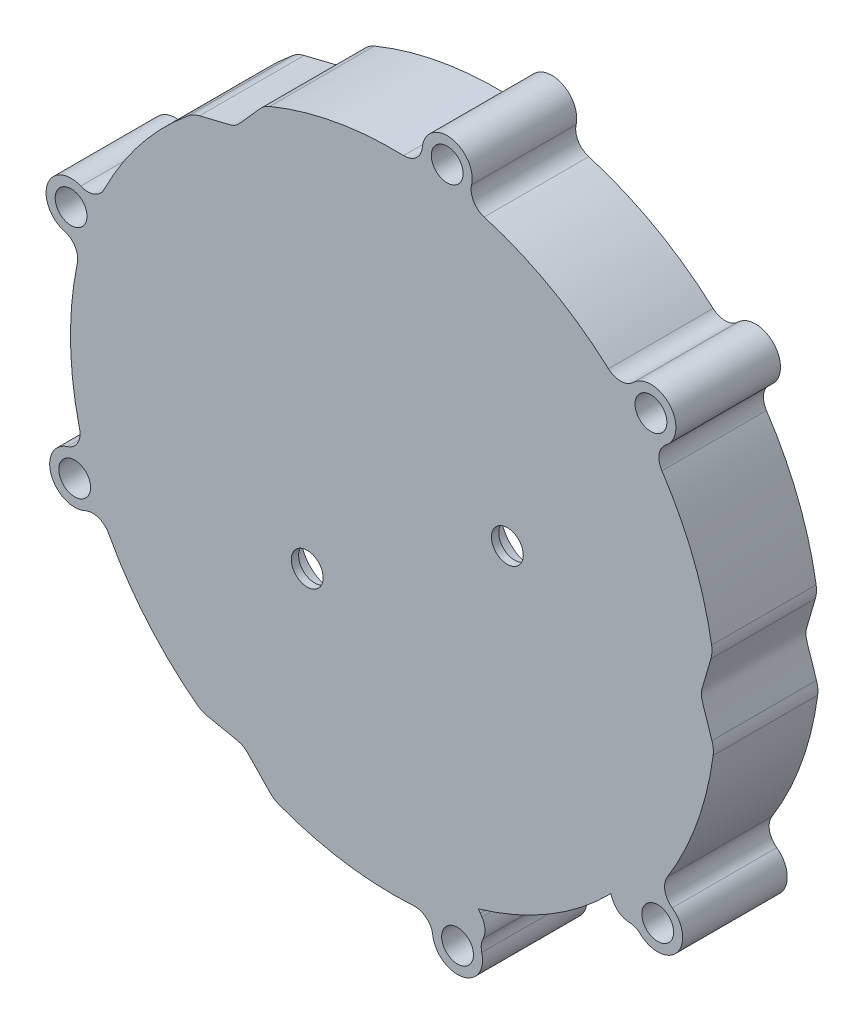
SolidWorks part; units mm, degrees
ref_plane "前视基准面" through (0, 0, 0) normal (0, 0, 1) x (1, 0, 0)
ref_plane "上视基准面" through (0, 0, 0) normal (0, 1, 0) x (1, 0, 0)
ref_plane "右视基准面" through (0, 0, 0) normal (1, 0, 0) x (0, 0, -1)
other "Configuration Table"
sketch "草图3" plane through (0, 0, -96.0145) normal (0, 0, 1) x (1, 0, 0)
  line L0 (-901.3742, -492.7064) -> (-40.5392, 22.1874) construction
  line L1 (-40.493, 24.6873) -> (-40.6757, 24.9625)
  line L3 (-26.0215, 33.3432) -> (-26.1775, 33.6344)
  line L5 (-23.7971, 32.2015) -> (837.0379, 547.0953) construction
  line L6 (-66.9395, 85.3275) -> (-545.4853, 885.3934) construction
  arc A0 (-71.5536, 85.4824) -> (-72.7752, 84.88) centre (-70.8722, 82.5608) ccw
  arc A1 (-64.9322, 89.4483) -> (-63.8246, 90.241) centre (-62.678, 87.4687) cw
  arc A2 (-15.3194, 61.8566) -> (-15.2303, 63.2157) centre (-18.1903, 62.7273) ccw
  arc A3 (-15.0628, 52.7838) -> (-15.1955, 54.1394) centre (-18.037, 53.177) ccw
  arc A4 (-43.4208, 19.0803) -> (-42.9297, 22.1412) centre (-43.1752, 20.6108) ccw
  arc A5 (-42.9297, 22.1412) -> (-43.4208, 19.0803) centre (-43.1752, 20.6108) ccw
  arc A6 (-70.6423, 28.7206) -> (-71.8826, 29.2835) centre (-70.055, 31.6626) cw
  arc A7 (-63.897, 24.9693) -> (-62.7646, 24.2125) centre (-61.7076, 27.0202) ccw
  arc A8 (-20.3655, 32.4479) -> (-21.9568, 35.1083) centre (-21.1611, 33.7781) ccw
  arc A9 (-21.9568, 35.1083) -> (-20.3655, 32.4479) centre (-21.1611, 33.7781) ccw
  arc A10 (-25.9128, 35.9041) -> (-66.9395, 85.3275) centre (-50.2567, 57.4361) ccw
  arc A11 (-66.9395, 85.3275) -> (-42.8007, 25.8029) centre (-50.2567, 57.4361) ccw
  arc A12 (-26.1775, 33.6344) -> (-25.9128, 35.9041) centre (-24.4147, 34.5791) cw
  arc A13 (-26.0215, 33.3432) -> (-24.3219, 32.2889) centre (-24.2586, 34.2879) ccw
  arc A14 (-40.493, 24.6873) -> (-40.368, 22.6912) centre (-42.1592, 23.581) cw
  arc A15 (-40.6757, 24.9625) -> (-42.8007, 25.8029) centre (-42.3419, 23.8562) ccw
  arc A134 (-23.0277, 31.7586) -> (-24.3219, 32.2889) centre (-24.3852, 30.2899) ccw
  arc A135 (-23.0277, 31.7586) -> (-19.7495, 31.4181) centre (-21.1611, 33.7781) ccw
  arc A136 (-19.7495, 31.4181) -> (-19.5648, 36.0174) centre (-21.1611, 33.7781) ccw
  arc A137 (-20.1027, 38.7014) -> (-19.5648, 36.0174) centre (-18.4039, 37.646) ccw
  arc A138 (-20.1027, 38.7014) -> (-15.0628, 52.7838) centre (-50.2567, 57.4361) ccw
  arc A139 (-14.8785, 53.9257) -> (-14.9764, 53.4929) centre (-12.9887, 53.2708) ccw
  arc A140 (-12.8929, 55.2685) -> (-14.8785, 53.9257) centre (-12.9887, 53.2708) ccw
  arc A141 (-12.8929, 55.2685) -> (-10.1628, 57.1148) centre (-12.7612, 58.0153) ccw
  arc A142 (-10.1628, 57.1148) -> (-12.9777, 60.7568) centre (-12.7612, 58.0153) ccw
  arc A143 (-15.115, 62.4671) -> (-12.9777, 60.7568) centre (-13.1352, 62.7506) ccw
  arc A144 (-15.2303, 63.2157) -> (-20.6958, 77.0932) centre (-50.2567, 57.4361) ccw
  arc A145 (-20.899, 77.4877) -> (-20.6958, 77.0932) centre (-19.0304, 78.2006) ccw
  arc A146 (-20.2411, 79.7926) -> (-20.899, 77.4877) centre (-19.0304, 78.2006) ccw
  arc A147 (-20.2411, 79.7926) -> (-19.3364, 82.9618) centre (-21.9058, 81.9815) ccw
  arc A148 (-19.3364, 82.9618) -> (-23.8338, 83.9424) centre (-21.9058, 81.9815) ccw
  arc A149 (-26.5705, 83.8787) -> (-23.8338, 83.9424) centre (-25.236, 85.3685) ccw
  arc A150 (-26.5705, 83.8787) -> (-40.2471, 91.4957) centre (-50.2567, 57.4361) ccw
  arc A151 (-40.6563, 91.6673) -> (-40.2471, 91.4957) centre (-39.6831, 93.4145) ccw
  arc A152 (-41.6339, 93.8558) -> (-40.6563, 91.6673) centre (-39.6831, 93.4145) ccw
  arc A153 (-41.6339, 93.8558) -> (-42.978, 96.8651) centre (-44.3161, 94.4625) ccw
  arc A154 (-42.978, 96.8651) -> (-47.0535, 94.7253) centre (-44.3161, 94.4625) ccw
  arc A155 (-49.109, 92.9175) -> (-47.0535, 94.7253) centre (-49.0443, 94.9165) ccw
  arc A156 (-49.109, 92.9175) -> (-63.8246, 90.241) centre (-50.2567, 57.4361) ccw
  arc A157 (-64.9057, 89.8297) -> (-64.482, 89.9613) centre (-65.2834, 91.7937) ccw
  arc A158 (-67.0614, 90.8779) -> (-64.9057, 89.8297) centre (-65.2834, 91.7937) ccw
  arc A159 (-67.0614, 90.8779) -> (-70.0254, 92.3191) centre (-69.5061, 89.6185) ccw
  arc A160 (-70.0254, 92.3191) -> (-71.772, 88.0603) centre (-69.5061, 89.6185) ccw
  arc A161 (-72.1845, 85.3542) -> (-71.772, 88.0603) centre (-73.4199, 86.927) ccw
  arc A162 (-72.7752, 84.88) -> (-82.0607, 73.208) centre (-50.2567, 57.4361) ccw
  arc A163 (-82.3007, 72.8348) -> (-82.0607, 73.208) centre (-83.8525, 74.0966) ccw
  arc A164 (-84.6258, 72.2521) -> (-82.3007, 72.8348) centre (-83.8525, 74.0966) ccw
  arc A165 (-84.6258, 72.2521) -> (-87.8227, 71.4509) centre (-85.6891, 69.716) ccw
  arc A166 (-87.8227, 71.4509) -> (-86.4232, 67.0658) centre (-85.6891, 69.716) ccw
  arc A167 (-84.9998, 64.7276) -> (-86.4232, 67.0658) centre (-86.9571, 65.1384) ccw
  arc A168 (-84.9998, 64.7276) -> (-84.758, 49.0749) centre (-50.2567, 57.4361) ccw
  arc A169 (-84.702, 48.6347) -> (-84.758, 49.0749) centre (-86.7017, 48.6038) ccw
  arc A170 (-86.1085, 46.6938) -> (-84.702, 48.6347) centre (-86.7017, 48.6038) ccw
  arc A171 (-86.1085, 46.6938) -> (-88.0425, 44.0251) centre (-85.2928, 44.0676) ccw
  arc A172 (-88.0425, 44.0251) -> (-84.1517, 41.5655) centre (-85.2928, 44.0676) ccw
  arc A173 (-81.5583, 40.6893) -> (-84.1517, 41.5655) centre (-83.3218, 39.7458) ccw
  arc A174 (-81.5583, 40.6893) -> (-71.8826, 29.2835) centre (-50.2567, 57.4361) ccw
  arc A175 (-70.9859, 28.5528) -> (-71.3117, 28.854) centre (-72.4979, 27.2437) ccw
  arc A176 (-70.8158, 26.1619) -> (-70.9859, 28.5528) centre (-72.4979, 27.2437) ccw
  arc A177 (-70.8158, 26.1619) -> (-70.5819, 22.8744) centre (-68.5028, 24.6744) ccw
  arc A178 (-70.5819, 22.8744) -> (-66.0204, 23.4912) centre (-68.5028, 24.6744) ccw
  arc A179 (-63.4705, 24.487) -> (-66.0204, 23.4912) centre (-64.215, 22.6307) ccw
  arc A180 (-62.7646, 24.2125) -> (-48.0136, 22.007) centre (-50.2567, 57.4361) ccw
  arc A181 (-47.5704, 21.9858) -> (-48.0136, 22.007) centre (-47.8872, 20.011) ccw
  arc A182 (-45.9032, 20.2635) -> (-47.5704, 21.9858) centre (-47.8872, 20.011) ccw
  arc A183 (-45.9032, 20.2635) -> (-43.6109, 17.8955) centre (-43.1752, 20.6108) ccw
  arc A184 (-43.6109, 17.8955) -> (-40.513, 21.3001) centre (-43.1752, 20.6108) ccw
  arc A185 (-40.368, 22.6912) -> (-40.513, 21.3001) centre (-38.5769, 21.8014) ccw
  conic Q0 (-71.5536, 85.4824) -> (-64.9322, 89.4483) control (-67.6066, 86.4029) rho 0.891852
  conic Q1 (-15.3194, 61.8566) -> (-15.1955, 54.1394) control (-16.4957, 57.9781) rho 0.891852
  conic Q2 (-63.897, 24.9693) -> (-70.6423, 28.7206) control (-66.6678, 27.9272) rho 0.891852
  point P64 (-50.2567, 57.4361)
  dimension "D1" = 3
  dimension "D2" = 3
  dimension "D3" = 3
  dimension "D4" = 3
  dimension "D5" = 3
  dimension "D6" = 3
  dimension "D7" = 2
extrude "凸台-拉伸2" add sketch "草图3" along normal offset from surface (11.5 mm away) 3 contours Q2 A7 A180 A181 A182 A183 A184 A185 A14 L1 A15 A11 A10 A12 L3 A13 A134 A135 A136 A137 A138 A3 Q1 A2 A144 A145 A146 A147 A148 A149 A150 A151 A152 A153 A154 A155 A156 A1 Q0 A0 A162 A163 A164 A165 A166 A167 A168 A169 A170 A171 A172
sketch "草图5" plane through (0, 0, -84.5145) normal (0, 0, 1) x (1, 0, 0)
  arc A0 (-25.9128, 35.9041) -> (-42.8007, 25.8029) centre (-50.2567, 57.4361) ccw construction
  arc A1 (-25.9128, 35.9041) -> (-42.8007, 25.8029) centre (-50.2567, 57.4361) ccw construction
  circle A3 centre (-50.2567, 57.4361) radius 33.5
extrude "凸台-拉伸3" add sketch "草图5" against normal up to surface (3 mm away) contours A3
sketch "草图6" plane through (0, 0, -84.5145) normal (0, 0, 1) x (1, 0, 0)
  arc A0 (-84.3313, 68.612) -> (-87.0469, 70.82) centre (-85.6891, 69.716) ccw
  circle A1 centre (-21.1611, 33.7781) radius 1.55
  circle A2 centre (-21.1611, 33.7781) radius 1.55 construction
  circle A3 centre (-43.1752, 20.6108) radius 1.55
  circle A4 centre (-43.1752, 20.6108) radius 1.55 construction
  arc A5 (-87.0469, 70.82) -> (-84.3313, 68.612) centre (-85.6891, 69.716) ccw
  arc A6 (-20.4576, 82.534) -> (-23.3539, 81.4289) centre (-21.9058, 81.9815) ccw
  arc A7 (-23.3539, 81.4289) -> (-20.4576, 82.534) centre (-21.9058, 81.9815) ccw
  arc A8 (-20.4576, 82.534) -> (-23.3539, 81.4289) centre (-21.9058, 81.9815) ccw construction
  arc A9 (-23.3539, 81.4289) -> (-20.4576, 82.534) centre (-21.9058, 81.9815) ccw construction
  arc A10 (-43.5619, 95.8167) -> (-45.0703, 93.1084) centre (-44.3161, 94.4625) ccw
  arc A11 (-45.0703, 93.1084) -> (-43.5619, 95.8167) centre (-44.3161, 94.4625) ccw
  arc A12 (-43.5619, 95.8167) -> (-45.0703, 93.1084) centre (-44.3161, 94.4625) ccw construction
  arc A13 (-45.0703, 93.1084) -> (-43.5619, 95.8167) centre (-44.3161, 94.4625) ccw construction
  arc A14 (-86.8427, 44.0436) -> (-83.743, 44.0915) centre (-85.2928, 44.0676) ccw
  arc A15 (-83.743, 44.0915) -> (-86.8427, 44.0436) centre (-85.2928, 44.0676) ccw
  arc A16 (-86.8427, 44.0436) -> (-83.743, 44.0915) centre (-85.2928, 44.0676) ccw construction
  arc A17 (-83.743, 44.0915) -> (-86.8427, 44.0436) centre (-85.2928, 44.0676) ccw construction
  arc A18 (-86.8917, 70.6939) -> (-84.4864, 68.7381) centre (-85.6891, 69.716) ccw
  arc A19 (-84.4864, 68.7381) -> (-86.8917, 70.6939) centre (-85.6891, 69.716) ccw
  arc A20 (-86.8917, 70.6939) -> (-84.4864, 68.7381) centre (-85.6891, 69.716) ccw construction
  arc A21 (-84.4864, 68.7381) -> (-86.8917, 70.6939) centre (-85.6891, 69.716) ccw construction
  arc A22 (-83.543, 44.0946) -> (-87.0426, 44.0405) centre (-85.2928, 44.0676) ccw
  arc A23 (-87.0426, 44.0405) -> (-83.543, 44.0946) centre (-85.2928, 44.0676) ccw
  circle A24 centre (-43.1752, 20.6108) radius 1.75
  circle A25 centre (-21.1611, 33.7781) radius 1.75
  arc A26 (-20.2707, 82.6053) -> (-23.5408, 81.3576) centre (-21.9058, 81.9815) ccw
  arc A27 (-23.5408, 81.3576) -> (-20.2707, 82.6053) centre (-21.9058, 81.9815) ccw
  arc A28 (-43.4646, 95.9914) -> (-45.1676, 92.9337) centre (-44.3161, 94.4625) ccw
  arc A29 (-45.1676, 92.9337) -> (-43.4646, 95.9914) centre (-44.3161, 94.4625) ccw
  dimension "D1" = 0
  dimension "D2" = 0
  dimension "D3" = 0
  dimension "D4" = 0
  dimension "D5" = 0
  dimension "D6" = 0
  dimension "D7" = 0.2
extrude "切除-拉伸1" cut sketch "草图6" against normal up to surface (11.5 mm away)
sketch "草图7" plane through (0, 0, -84.5145) normal (0, 0, 1) x (1, 0, 0)
  line L0 (-43.1752, 20.6108) -> (-21.1605, 33.7789) construction
  line L1 (-31.7197, 27.7937) -> (-35.7883, 34.5957) construction
  line L2 (-48.1688, 36.3931) -> (-39.8424, 41.3735) construction
  circle A1 centre (-37.6984, 61.4255) radius 1.75
  circle A3 centre (-21.1611, 33.7781) radius 1.75
  circle A6 centre (-21.1611, 33.7781) radius 1.75 construction
  circle A7 centre (-43.1752, 20.6108) radius 1.75
  circle A8 centre (-43.1752, 20.6108) radius 1.75 construction
  circle A9 centre (-59.7122, 48.2576) radius 1.75
  point P7 (0, 0)
  point P8 (0, 0)
  dimension "D1" = 0
  dimension "D2" = 0
extrude "切除-拉伸5" cut sketch "草图7" against normal through all
sketch "草图10" plane through (0, 0, -87.5145) normal (0, 0, -1) x (-1, 0, 0)
  circle A0 centre (37.6984, 61.4255) radius 3.75
  circle A1 centre (59.7122, 48.2576) radius 1.75
  circle A2 centre (59.7122, 48.2576) radius 1.75 construction
  circle A3 centre (37.6984, 61.4255) radius 1.75
  circle A4 centre (37.6984, 61.4255) radius 1.75 construction
  circle A5 centre (59.7122, 48.2576) radius 3.75
  dimension "D1" = 0
  dimension "D2" = 0
  dimension "D3" = 2
extrude "切除-拉伸6" cut sketch "草图10" against normal blind 2.2
